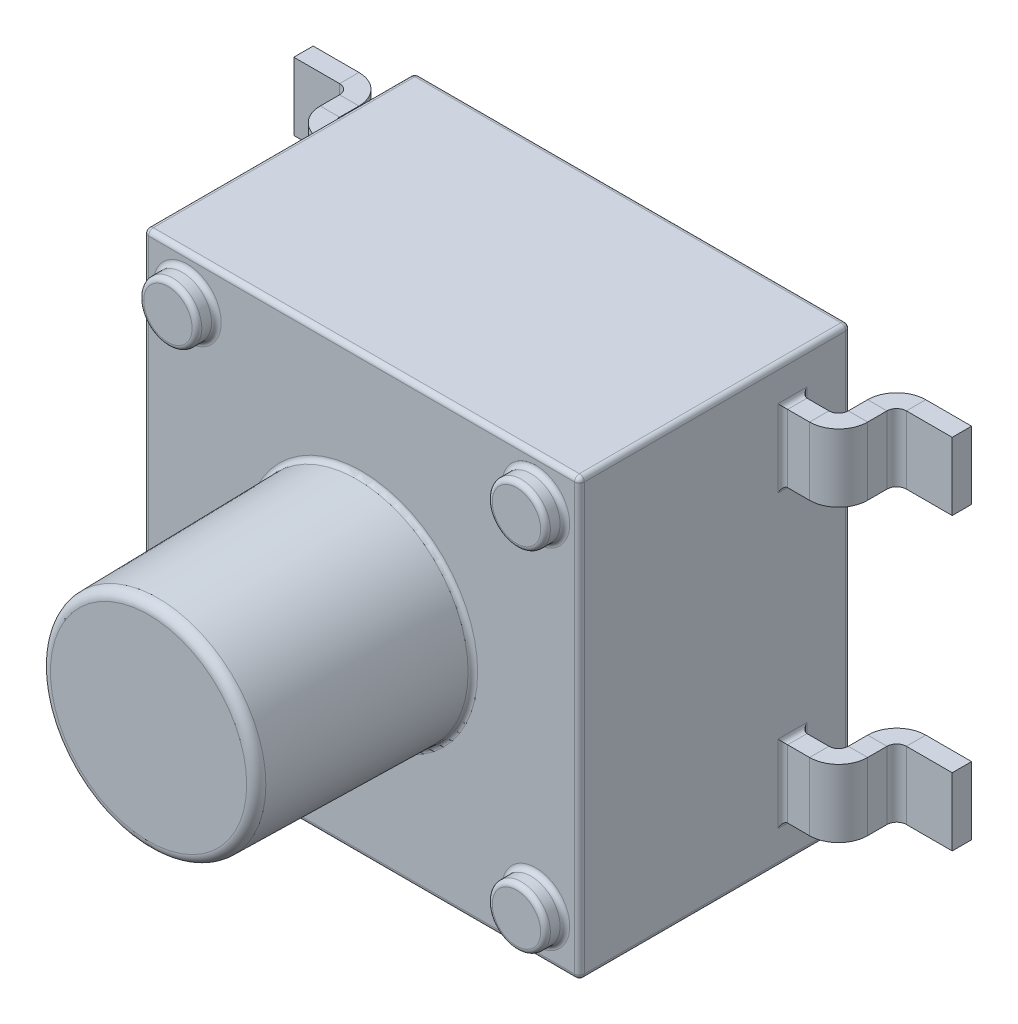
SolidWorks part; units mm, degrees
ref_plane "Front Plane" through (0, 0, 0) normal (0, 0, 1) x (1, 0, 0)
ref_plane "Top Plane" through (0, 0, 0) normal (0, 1, 0) x (1, 0, 0)
ref_plane "Right Plane" through (0, 0, 0) normal (1, 0, 0) x (0, 0, -1)
sketch "Sketch1" plane through (0, 0, 0) normal (0, 0, 1) x (1, 0, 0)
  line L1 (-2.25, 2.25) -> (2.25, 2.25)
  line L2 (-2.25, 2.25) -> (-2.25, -2.25)
  line L3 (-2.25, -2.25) -> (2.25, -2.25)
  line L4 (2.25, 2.25) -> (2.25, -2.25)
  line L5 (-2.25, 2.25) -> (2.25, -2.25) construction
  line L6 (-2.25, -2.25) -> (2.25, 2.25) construction
  point P0 (0, 0)
  dimension "D1" = 4.5
  dimension "D2" = 4.5
extrude "Boss-Extrude1" add sketch "Sketch1" along normal blind 2.5
sketch "Sketch2" plane through (0, 0, 2.5) normal (0, 0, 1) x (1, 0, 0)
  line L1 (-2.25, 2.25) -> (2.25, 2.25)
  line L2 (-2.25, 2.25) -> (-2.25, -2.25)
  line L3 (-2.25, -2.25) -> (2.25, -2.25)
  line L4 (2.25, 2.25) -> (2.25, -2.25)
  line L5 (-2.25, 2.25) -> (2.25, -2.25) construction
  line L6 (-2.25, -2.25) -> (2.25, 2.25) construction
  point P0 (0, 0)
extrude "Boss-Extrude2" add sketch "Sketch2" along normal blind 0.3
sketch "Sketch3" plane through (0, 0, 2.8) normal (0, 0, 1) x (1, 0, 0)
  line L0 (0, 4.3748) -> (0, -3.2039) construction
  line L1 (5.0333, 0) -> (-6.3552, 0) construction
  circle A0 centre (-1.8, 1.8) radius 0.3
  circle A1 centre (1.8, 1.8) radius 0.3
  circle A2 centre (1.8, -1.8) radius 0.3
  circle A3 centre (-1.8, -1.8) radius 0.3
  dimension "D1" = 0.6
  dimension "D2" = 1.8
  dimension "D3" = 1.8
extrude "Boss-Extrude3" add sketch "Sketch3" along normal blind 0.2
sketch "Sketch4" plane through (0, 0, 2.8) normal (0, 0, 1) x (1, 0, 0)
  circle A0 centre (0, 0) radius 1.15
  dimension "D1" = 2.3
extrude "Boss-Extrude4" add sketch "Sketch4" along normal blind 2.2 draft 1
sketch "Sketch5" plane through (0, 0, 0) normal (0, 1, 0) x (1, 0, 0)
  line L0 (2.25, -0.6) -> (2.5267, -0.6)
  line L1 (2.25, -2.8) -> (2.25, 0) construction
  line L2 (2.7267, -0.4) -> (2.7267, -0.2)
  line L3 (2.9267, 0) -> (3.4, 0)
  line L4 (2.25, 0) -> (-2.25, 0) construction
  arc A0 (2.7267, -0.2) -> (2.9267, 0) centre (2.9267, -0.2) cw
  arc A1 (2.5267, -0.6) -> (2.7267, -0.4) centre (2.5267, -0.4) ccw
  dimension "D2" = 0.2
  dimension "D1" = 3.4
  dimension "D3" = 0.6
sketch "Sketch6" plane through (2.25, 0, 0) normal (1, 0, 0) x (0, 0, -1)
  line L0 (0, -2.25) -> (0, 2.25) construction
  line L2 (-0.7, 1.85) -> (-0.5, 1.85)
  line L3 (-0.7, 1.85) -> (-0.7, 1.15)
  line L4 (-0.7, 1.15) -> (-0.5, 1.15)
  line L5 (-0.5, 1.85) -> (-0.5, 1.15)
  line L6 (-0.7, 1.85) -> (-0.5, 1.15) construction
  line L7 (-0.7, 1.15) -> (-0.5, 1.85) construction
  point P3 (-0.6, 1.5)
  dimension "D1" = 0.2
  dimension "D2" = 0.7
  dimension "D3" = 1.5
  dimension "D4" = 0.6
sweep "Sweep4" add profiles "Sketch6" path "Sketch5"
mirror "Mirror1" about plane through (0, 0, 0) normal (0, 1, 0) of "Sweep4"
mirror "Mirror2" about plane through (0, 0, 0) normal (1, 0, 0) of "Sweep4", "Mirror1"
fillet "Fillet1" radius 0.1 1 edges at (1.1116, 0, 5)
fillet "Fillet2" radius 0.05 4 edges at (2.1, -1.8, 3) (-2.1, -1.8, 3) (1.5, 1.8, 3) (-1.5, 1.8, 3)
fillet "Fillet3" radius 0.05 33 edges at (-2.25, 0, 0) (-2.25, 1.5, 0.7) (-2.25, 1.85, 0.6) (-2.25, 1.5, 0.5) (-2.25, 1.15, 0.6) (-2.25, -1.5, 0.5) (-2.25, -1.85, 0.6) (-2.25, -1.5, 0.7) (-2.25, -1.15, 0.6) (-2.25, -2.25, 1.4) (0, -2.25, 0) (2.25, -2.25, 1.4) (2.25, 0, 0) (2.25, 1.5, 0.5) (2.25, 1.85, 0.6) (2.25, 1.5, 0.7) (2.25, 1.15, 0.6) (2.25, -1.5, 0.7) (2.25, -1.85, 0.6) (2.25, -1.5, 0.5) (2.25, -1.15, 0.6) (2.25, 2.25, 1.4) (-2.25, 2.25, 1.4) (0, 2.25, 0) (0, -2.25, 2.8) (-2.25, 0, 2.8) (0, 2.25, 2.8) (2.25, 0, 2.8) (-1.5, 1.8, 2.8) (1.5, 1.8, 2.8) (2.1, -1.8, 2.8) (-2.1, -1.8, 2.8) (1.15, 0, 2.8)
